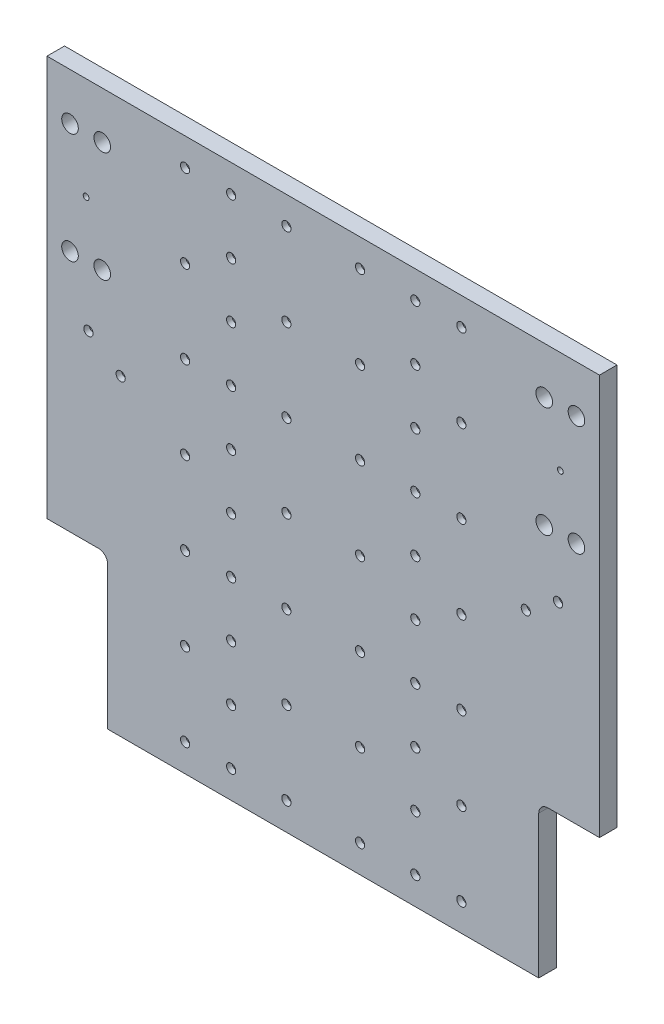
SolidWorks part; units mm, degrees
ref_plane "Front Plane" through (0, 0, 0) normal (0, 0, 1) x (1, 0, 0)
ref_plane "Top Plane" through (0, 0, 0) normal (0, 1, 0) x (1, 0, 0)
ref_plane "Right Plane" through (0, 0, 0) normal (1, 0, 0) x (0, 0, -1)
sketch "Sketch1" plane through (0, 0, 0) normal (0, 0, 1) x (1, 0, 0)
  line L1 (-300, 300) -> (300, 300)
  line L2 (-300, 300) -> (-300, -300)
  line L3 (-300, -300) -> (300, -300)
  line L4 (300, 300) -> (300, -300)
  dimension "D1" = 600
extrude "Boss-Extrude1" add sketch "Sketch1" along normal blind 19.05
sketch "Sketch2" plane through (0, 0, 0) normal (0, 0, -1) x (-1, 0, 0)
  line L0 (300, -300) -> (-300, -300) construction
  line L1 (300, 300) -> (300, -300) construction
  line L2 (234.05, -135) -> (300, -135) construction
  line L3 (234.05, -300) -> (234.05, -125) construction
  line L4 (-234.05, -125) -> (-234.05, -300) construction
  line L5 (-234.05, -135) -> (-300, -135) construction
  line L6 (300, -300) -> (234.05, -300)
  line L7 (300, -135) -> (300, -300)
  line L8 (234.05, -135) -> (300, -135)
  line L9 (234.05, -300) -> (234.05, -135)
  line L10 (-234.05, -135) -> (-234.05, -300)
  line L11 (-234.05, -135) -> (-300, -135)
  line L12 (-234.05, -300) -> (-300, -300)
  line L13 (-300, -135) -> (-300, -300)
extrude "Cut-Extrude1" cut sketch "Sketch2" against normal through all
fillet "Fillet1" radius 10 2 edges at (-234.05, -135, 9.525) (234.05, -135, 9.525)
sketch "Sketch5" plane through (0, 0, 0) normal (0, 0, -1) x (-1, 0, 0)
  circle A0 centre (240, 249) radius 9.017 construction
  circle A1 centre (275, 249) radius 9.017 construction
  circle A2 centre (257.5, 189) radius 3.175 construction
  circle A3 centre (275, 129) radius 9.017 construction
  circle A4 centre (240, 129) radius 9.017 construction
  circle A5 centre (-275, 129) radius 9.017 construction
  circle A6 centre (-240, 129) radius 9.017 construction
  circle A7 centre (-257.5, 189) radius 3.175 construction
  circle A8 centre (-275, 249) radius 9.017 construction
  circle A9 centre (-240, 249) radius 9.017 construction
  circle A10 centre (240, 249) radius 9.017
  circle A11 centre (275, 249) radius 9.017
  circle A12 centre (257.5, 189) radius 3.175
  circle A13 centre (275, 129) radius 9.017
  circle A14 centre (240, 129) radius 9.017
  circle A15 centre (-275, 129) radius 9.017
  circle A16 centre (-240, 129) radius 9.017
  circle A17 centre (-257.5, 189) radius 3.175
  circle A18 centre (-275, 249) radius 9.017
  circle A19 centre (-240, 249) radius 9.017
extrude "Cut-Extrude2" cut sketch "Sketch5" against normal through all
sketch "Sketch6" plane through (0, 0, 19.05) normal (0, 0, 1) x (1, 0, 0)
  line L0 (0, 0) -> (0, -72.3875)
  circle A0 centre (-150, -270) radius 2.5 construction
  circle A1 centre (-150, -180) radius 2.5 construction
  circle A2 centre (-150, -90) radius 2.5 construction
  circle A3 centre (-150, 0) radius 2.5 construction
  circle A4 centre (-150, 90) radius 2.5 construction
  circle A5 centre (-150, 180) radius 2.5 construction
  circle A6 centre (-150, 270) radius 2.5 construction
  circle A7 centre (150, 270) radius 2.5 construction
  circle A8 centre (150, 180) radius 2.5 construction
  circle A9 centre (150, 90) radius 2.5 construction
  circle A10 centre (150, 0) radius 2.5 construction
  circle A11 centre (150, -90) radius 2.5 construction
  circle A12 centre (150, -180) radius 2.5 construction
  circle A13 centre (150, -270) radius 2.5 construction
  circle A14 centre (-150, -270) radius 2.5
  circle A15 centre (-150, -180) radius 2.5
  circle A16 centre (-150, -90) radius 2.5
  circle A17 centre (-150, 0) radius 2.5
  circle A18 centre (-150, 90) radius 2.5
  circle A19 centre (-150, 180) radius 2.5
  circle A20 centre (-150, 270) radius 2.5
  circle A21 centre (150, 270) radius 2.5
  circle A22 centre (150, 180) radius 2.5
  circle A23 centre (150, 90) radius 2.5
  circle A24 centre (150, 0) radius 2.5
  circle A25 centre (150, -90) radius 2.5
  circle A26 centre (150, -180) radius 2.5
  circle A27 centre (150, -270) radius 2.5
  circle A28 centre (40, 270) radius 2.5
  circle A29 centre (40, 180) radius 2.5
  circle A30 centre (40, 0) radius 2.5
  circle A31 centre (40, -90) radius 2.5
  circle A32 centre (40, -180) radius 2.5
  circle A33 centre (40, 90) radius 2.5
  circle A34 centre (40, -270) radius 2.5
  circle A35 centre (-40, -270) radius 2.5
  circle A36 centre (-40, 90) radius 2.5
  circle A37 centre (-40, -180) radius 2.5
  circle A38 centre (-40, -90) radius 2.5
  circle A39 centre (-40, 0) radius 2.5
  circle A40 centre (-40, 180) radius 2.5
  circle A41 centre (-40, 270) radius 2.5
hole_wizard "CBORE for M5 SHCS1" positions "Sketch3" profile "Sketch4" counterbore size "M5" standard "ANSI Metric"
sketch "Sketch3" plane through (0, 0, 19.05) normal (0, 0, 1) x (1, 0, 0)
  point P0 (-100, 210)
  point P3 (-100, 270)
  point P6 (100, 270)
  point P9 (100, 210)
  point P12 (100, 150)
  point P15 (-100, 150)
  point P18 (-100, 90)
  point P21 (100, 90)
  point P24 (100, 30)
  point P27 (-100, 30)
  point P30 (-255, 64)
  point P33 (-220, 39)
  point P36 (255, 64)
  point P39 (220, 39)
  point P42 (100, -30)
  point P45 (-100, -30)
  point P48 (-100, -90)
  point P51 (100, -90)
  point P54 (100, -150)
  point P57 (-100, -150)
  point P60 (-100, -210)
  point P63 (100, -210)
  point P66 (100, -270)
  point P69 (-100, -270)
  point P72 (150, -270)
  point P75 (150, -180)
  point P78 (150, -90)
  point P81 (150, 0)
  point P84 (150, 90)
  point P87 (150, 180)
  point P90 (150, 270)
  point P93 (40, 270)
  point P96 (40, 180)
  point P99 (-40, 180)
  point P102 (-40, 270)
  point P105 (-150, 270)
  point P108 (-150, 180)
  point P111 (-150, 90)
  point P114 (-40, 90)
  point P117 (40, 90)
  point P120 (40, 0)
  point P123 (-40, 0)
  point P126 (-40, -90)
  point P129 (40, -90)
  point P132 (-150, -90)
  point P135 (-150, 0)
  point P138 (-150, -90)
  point P141 (-150, 0)
  point P143 (-220, 39)
  point P145 (-255, 64)
  point P147 (-150, -90)
  point P149 (-150, -180)
  point P152 (-150, -270)
  point P155 (-40, -270)
  point P158 (-40, -180)
  point P161 (40, -180)
  point P164 (40, -270)
sketch "Sketch4" plane through (-100, 210, 19.05) normal (1, 0, 0) x (0, -1, 0)
  line L0 (0, 0) -> (0, 30)
  line L1 (0, 30) -> (2.75, 28.3476)
  line L2 (2.75, 28.3476) -> (2.75, 6)
  line L3 (2.75, 6) -> (5, 6)
  line L4 (5, 6) -> (5, 0)
  line L5 (5, 0) -> (0, 0)
  line L10 (0, 30) -> (-2.75, 28.3476) construction
  line L11 (0, -6.35) -> (0, 107.95) construction
  dimension "Hole Dia." = 5.5
  dimension "Hole Depth" = 30
  dimension "C'Bore Dia." = 10
  dimension "C'Bore Depth" = 6
  dimension "Drill Angle" = 118
